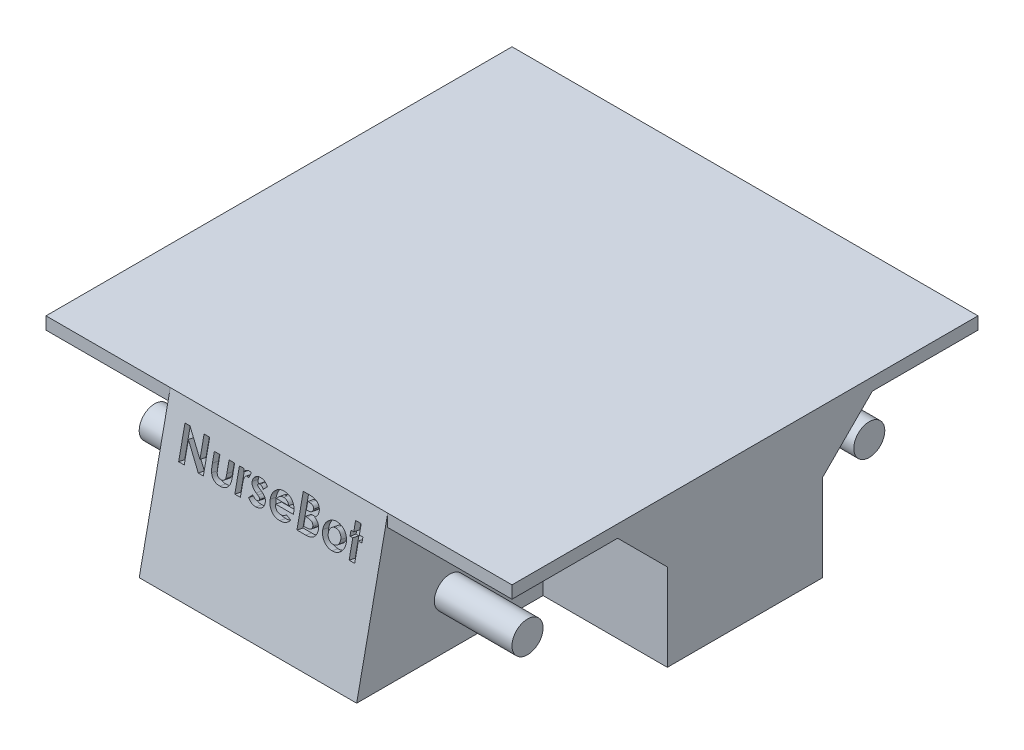
SolidWorks part; units mm, degrees
ref_plane "Front Plane" through (0, 0, 0) normal (0, 0, 1) x (1, 0, 0)
ref_plane "Top Plane" through (0, 0, 0) normal (0, 1, 0) x (1, 0, 0)
ref_plane "Right Plane" through (0, 0, 0) normal (1, 0, 0) x (0, 0, -1)
sketch "Sketch1" plane through (0, 0, 0) normal (0, 1, 0) x (1, 0, 0)
  line L1 (-375, 375) -> (375, 375)
  line L2 (-375, 375) -> (-375, -375)
  line L3 (-375, -375) -> (375, -375)
  line L4 (375, 375) -> (375, -375)
  line L5 (-375, 375) -> (375, -375) construction
  line L6 (-375, -375) -> (375, 375) construction
  line L7 (115, 95) -> (375, 95) construction
  line L8 (115, 95) -> (115, 375) construction
  line L9 (115, 375) -> (375, 375) construction
  line L10 (375, 95) -> (375, 375) construction
  line L11 (-115, 95) -> (-375, 95) construction
  line L12 (-115, 95) -> (-115, 375) construction
  line L13 (-115, 375) -> (-375, 375)
  line L14 (-375, 95) -> (-375, 375)
  point P0 (0, 0)
  dimension "700" = 750
  dimension "D2" = 750
  dimension "D3" = 280
  dimension "280" = 280
  dimension "D4" = 260
  dimension "D5" = 260
extrude "Boss-Extrude1" add sketch "Sketch1" along normal blind 20 contours L4 L1 L2 L3
sketch "Sketch6" plane through (0, 0, 0) normal (0, -1, 0) x (-1, 0, 0)
  line L0 (175, -375) -> (175, -125)
  line L1 (375, -375) -> (-375, -375) construction
  line L2 (175, -125) -> (375, -125)
  line L3 (375, 375) -> (375, -375) construction
  line L4 (375, -125) -> (375, 125)
  line L5 (375, 125) -> (175, 125)
  line L6 (175, 125) -> (175, 375)
  line L7 (375, 375) -> (-375, 375) construction
  line L8 (175, 375) -> (-175, 375)
  line L9 (-175, 375) -> (-175, 125)
  line L10 (-175, 125) -> (-375, 125)
  line L11 (-375, 375) -> (-375, -375) construction
  line L12 (-375, 125) -> (-375, -125)
  line L13 (-375, -125) -> (-175, -125)
  line L14 (-175, -125) -> (-175, -375)
  line L15 (-175, -375) -> (175, -375)
  line L16 (0, -375) -> (0, 375) construction
  line L17 (375, 0) -> (-375, 0) construction
  line L18 (275, -375) -> (275, 375) construction
  line L19 (-275, -375) -> (-275, 375) construction
  line L20 (375, -250) -> (-375, -250) construction
  line L21 (375, 250) -> (-375, 250) construction
  dimension "D1" = 550
  dimension "D2" = 500
  dimension "D3" = 250
extrude "Boss-Extrude5" add sketch "Sketch6" along normal blind 220
sketch "Sketch7" plane through (0, 0, 0) normal (1, 0, 0) x (0, 0, -1)
  line L0 (0, -220) -> (0, 20) construction
  line L1 (-125, -220) -> (125, -220) construction
  line L2 (375, 20) -> (-375, 20) construction
  line L3 (-375, 0) -> (-125, 0) construction
  circle A0 centre (275, -140) radius 25
  circle A1 centre (-275, -140) radius 25
  dimension "D1" = 50
  dimension "D2" = 550
  dimension "D3" = 140
extrude "Boss-Extrude6" add sketch "Sketch7" along normal blind 300 and the other way blind 300
chamfer "Chamfer2" distance 80 angle 45 4 edges at (275, 0, -125) (275, 0, 125) (-275, 0, 125) (-275, 0, -125)
sketch "Sketch8" plane through (175, 0, 0) normal (1, 0, 0) x (0, 0, -1)
  line L0 (-375, -220) -> (-375, 20)
  line L1 (-375, 20) -> (-425, -220)
  line L2 (-425, -220) -> (-375, -220)
  dimension "D1" = 50
extrude "Boss-Extrude7" add sketch "Sketch8" against normal up to surface (350 mm away) up to face at (-175, -140, 250)
sketch "Sketch9" plane through (0, 75.7072, 363.3943) normal (0, 0.204, 0.979) x (1, 0, 0)
  text T0 "<b>NurseBot</b>" font "Century Gothic" height 50
extrude "Cut-Extrude1" cut sketch "Sketch9" against normal blind 10
